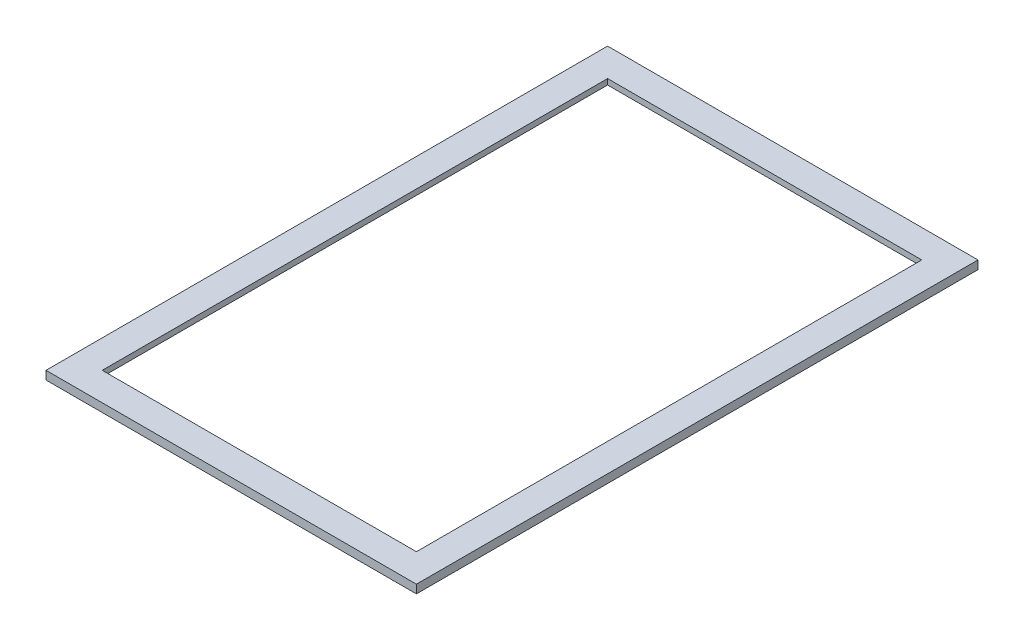
SolidWorks part; units mm, degrees
ref_plane "Спереди" through (0, 0, 0) normal (0, 0, 1) x (1, 0, 0)
ref_plane "Сверху" through (0, 0, 0) normal (0, 1, 0) x (1, 0, 0)
ref_plane "Справа" through (0, 0, 0) normal (1, 0, 0) x (0, 0, -1)
sketch "Эскиз1" plane through (0, 0, 0) normal (0, 1, 0) x (1, 0, 0)
  line L1 (-65.875, -99.875) -> (65.875, -99.875)
  line L2 (-65.875, -99.875) -> (-65.875, 99.875)
  line L3 (-65.875, 99.875) -> (65.875, 99.875)
  line L4 (65.875, -99.875) -> (65.875, 99.875)
  line L5 (-65.875, -99.875) -> (65.875, 99.875) construction
  line L6 (-65.875, 99.875) -> (65.875, -99.875) construction
  point P0 (0, 0)
  dimension "D1" = 199.75
  dimension "D2" = 131.75
extrude "Бобышка-Вытянуть1" add sketch "Эскиз1" along normal blind 3
sketch "Эскиз2" plane through (0, 3, 0) normal (0, 1, 0) x (1, 0, 0)
  line L0 (65.875, 99.875) -> (-65.875, 99.875) construction
  line L1 (-55.875, -89.875) -> (55.875, -89.875)
  line L2 (-55.875, -89.875) -> (-55.875, 89.875)
  line L3 (-55.875, 89.875) -> (55.875, 89.875)
  line L4 (55.875, -89.875) -> (55.875, 89.875)
  line L5 (-55.875, -89.875) -> (55.875, 89.875) construction
  line L6 (-55.875, 89.875) -> (55.875, -89.875) construction
  line L7 (65.875, -99.875) -> (65.875, 99.875) construction
  point P0 (0, 0)
  dimension "D1" = 10
  dimension "D2" = 10
extrude "Вырез-Вытянуть1" cut sketch "Эскиз2" against normal blind 6
sketch "Эскиз3" plane through (0, 0, 0) normal (0, -1, 0) x (1, 0, 0)
  line L0 (-55.875, 89.875) -> (55.875, 89.875) construction
  line L1 (-60.875, -94.875) -> (60.875, -94.875)
  line L2 (-60.875, -94.875) -> (-60.875, 94.875)
  line L3 (-60.875, 94.875) -> (60.875, 94.875)
  line L4 (60.875, -94.875) -> (60.875, 94.875)
  line L5 (-60.875, -94.875) -> (60.875, 94.875) construction
  line L6 (-60.875, 94.875) -> (60.875, -94.875) construction
  line L8 (-55.875, 89.875) -> (-55.875, -89.875) construction
  point P0 (0, 0)
  dimension "D1" = 5
  dimension "D2" = 5
extrude "Вырез-Вытянуть2" cut sketch "Эскиз3" against normal blind 1
sketch "Эскиз6" plane through (0, 0, 0) normal (0, -1, 0) x (1, 0, 0)
  line L1 (-60.875, 94.875) -> (60.875, 94.875)
  line L2 (-60.875, 94.875) -> (-60.875, -94.875)
  line L3 (-60.875, -94.875) -> (60.875, -94.875)
  line L4 (60.875, 94.875) -> (60.875, -94.875)
